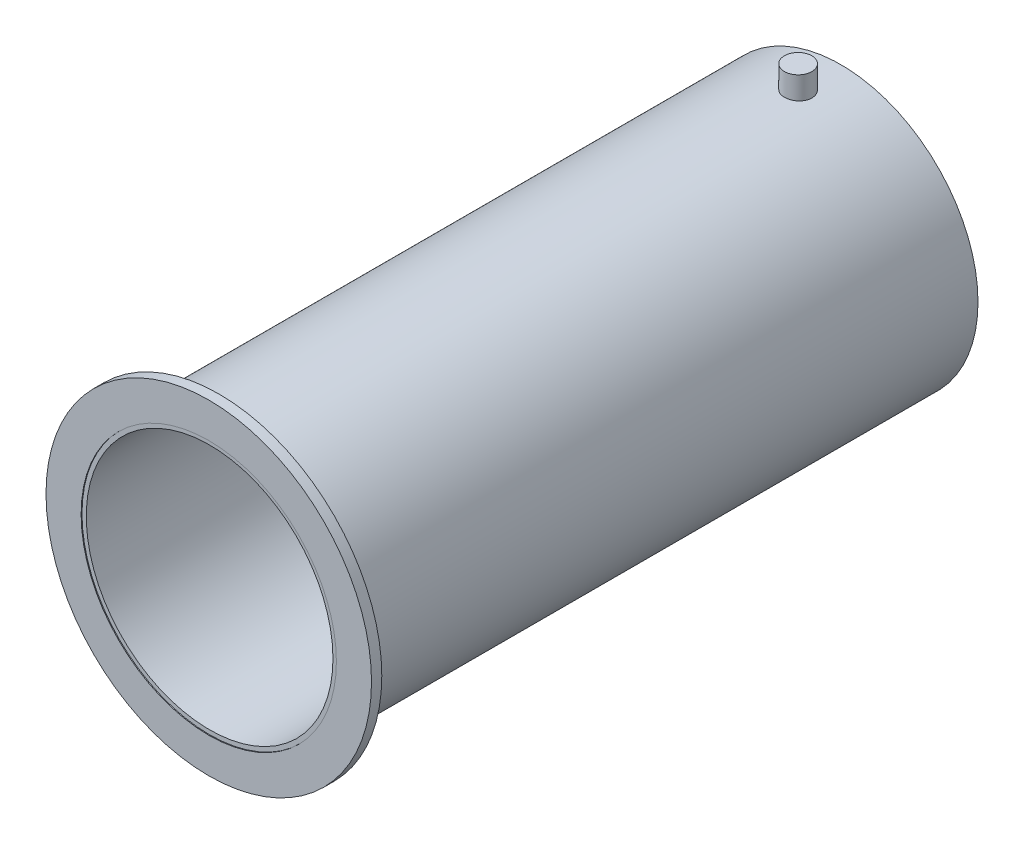
SolidWorks part; units mm, degrees
ref_plane "Front Plane" through (0, 0, 0) normal (0, 0, 1) x (1, 0, 0)
ref_plane "Top Plane" through (0, 0, 0) normal (0, 1, 0) x (1, 0, 0)
ref_plane "Right Plane" through (0, 0, 0) normal (1, 0, 0) x (0, 0, -1)
ref_plane "Plane_Z-12.0" through (0, 0, -12) normal (0, 0, 1) x (1, 0, 0)
sketch "Sketch1" plane through (0, 0, -12) normal (0, 0, 1) x (1, 0, 0)
  circle A0 centre (48, 0) radius 16
  circle A1 centre (48, 0) radius 13
extrude "Bottom_ring_bayonet" add sketch "Sketch1" along normal blind 8
ref_plane "Plane_Z-4.0" through (0, 0, -4) normal (0, 0, 1) x (1, 0, 0)
sketch "Sketch2" plane through (0, 0, -4) normal (0, 0, 1) x (1, 0, 0)
  circle A0 centre (48, 0) radius 16
  circle A1 centre (48, 0) radius 14.4
  dimension "WellOD" = 32
  dimension "WellBore" = 28.8
extrude "Well_tube" add sketch "Sketch2" along normal blind 65.7
ref_plane "Plane_Z+60.6" through (0, 0, 60.6) normal (0, 0, 1) x (1, 0, 0)
sketch "Sketch3" plane through (0, 0, 60.6) normal (0, 0, 1) x (1, 0, 0)
  circle A0 centre (48, 0) radius 19
  circle A1 centre (48, 0) radius 14.9
extrude "Hatch_flange" add sketch "Sketch3" along normal blind 1.2
ref_plane "Plane_Y+15.0" through (0, 15, 0) normal (0, 1, 0) x (1, 0, 0)
sketch "Sketch4" plane through (0, 15, 0) normal (0, 1, 0) x (1, 0, 0)
  circle A0 centre (48, 7) radius 1.6
extrude "Bayonet_pin_stbd" add sketch "Sketch4" along normal blind 3.6
ref_plane "Plane_Y-18.6" through (0, -18.6, 0) normal (0, 1, 0) x (1, 0, 0)
sketch "Sketch5" plane through (0, -18.6, 0) normal (0, 1, 0) x (1, 0, 0)
  circle A0 centre (48, 7) radius 1.6
extrude "Bayonet_pin_port" add sketch "Sketch5" along normal blind 3.6
